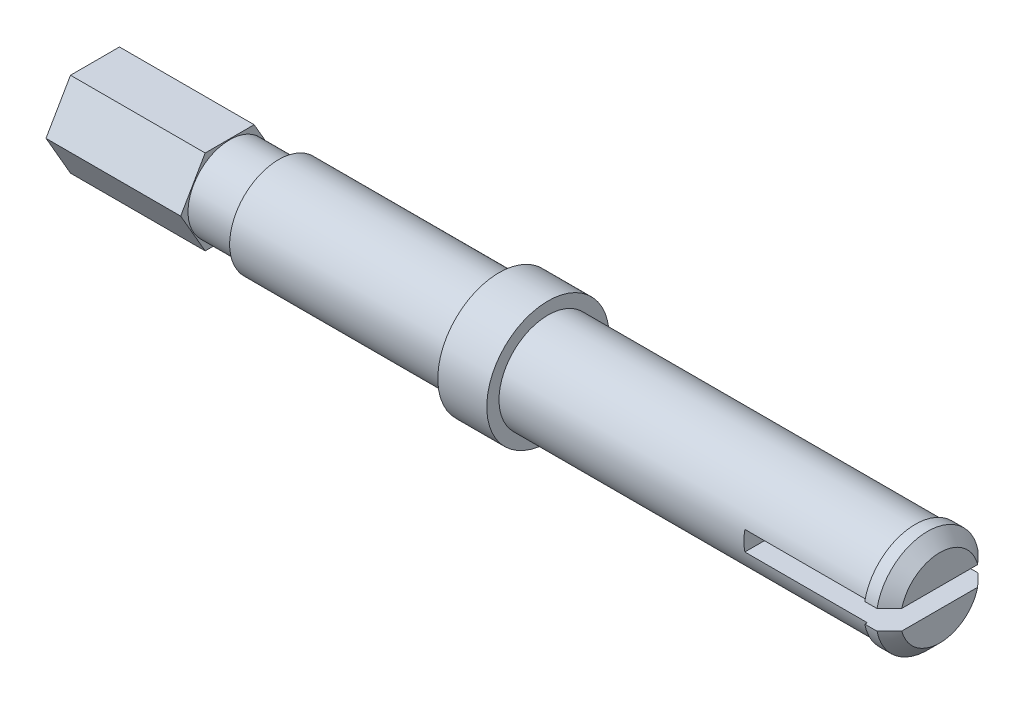
SolidWorks part; units mm, degrees
ref_plane "前视基准面" through (0, 0, 0) normal (0, 0, 1) x (1, 0, 0)
ref_plane "上视基准面" through (0, 0, 0) normal (0, 1, 0) x (1, 0, 0)
ref_plane "右视基准面" through (0, 0, 0) normal (1, 0, 0) x (0, 0, -1)
sketch "草图1" plane through (0, 0, 0) normal (1, 0, 0) x (0, 0, -1)
  line L1 (-2, 0) -> (-1, -1.7321)
  line L2 (-1, -1.7321) -> (1, -1.7321)
  line L3 (1, -1.7321) -> (2, 0)
  line L4 (2, 0) -> (1, 1.7321)
  line L5 (1, 1.7321) -> (-1, 1.7321)
  line L6 (-1, 1.7321) -> (-2, 0)
  circle A0 centre (0, 0) radius 1.7321 construction
  dimension "D1" = 4
extrude "凸台-拉伸1" add sketch "草图1" along normal blind 5.5
sketch "草图2" plane through (5.5, 0, 0) normal (1, 0, 0) x (0, 0, -1)
  circle A0 centre (0, 0) radius 1.7
  dimension "D1" = 3.4
extrude "凸台-拉伸2" add sketch "草图2" along normal blind 2
sketch "草图3" plane through (7.5, 0, 0) normal (1, 0, 0) x (0, 0, -1)
  circle A0 centre (0, 0) radius 2
  dimension "D1" = 4
extrude "凸台-拉伸3" add sketch "草图3" along normal blind 9
sketch "草图4" plane through (16.5, 0, 0) normal (1, 0, 0) x (0, 0, -1)
  circle A0 centre (0, 0) radius 2.5
  dimension "D1" = 5
extrude "凸台-拉伸4" add sketch "草图4" along normal blind 2
sketch "草图5" plane through (18.5, 0, 0) normal (1, 0, 0) x (0, 0, -1)
  circle A0 centre (0, 0) radius 2
  dimension "D1" = 4
extrude "凸台-拉伸5" add sketch "草图5" along normal blind 16
sketch "草图6" plane through (34.5, 0, 0) normal (1, 0, 0) x (0, 0, -1)
  circle A0 centre (0, 0) radius 2.1
  dimension "D1" = 4.2
extrude "凸台-拉伸6" add sketch "草图6" against normal blind 1
chamfer "倒角1" distance 0.5 angle 45 1 edges at (34.5, 0, -2.1)
sketch "草图7" plane through (34.5, 0, 0) normal (1, 0, 0) x (0, 0, -1)
  line L0 (2.5, 0.4) -> (2.5, -0.4)
  line L1 (2.5, 0.4) -> (-2.5, 0.4)
  line L2 (2.5, -0.4) -> (-2.5, -0.4)
  line L3 (-2.5, 0.4) -> (-2.5, -0.4)
  line L4 (2.5, 0.4) -> (-2.5, -0.4) construction
  line L5 (2.5, -0.4) -> (-2.5, 0.4) construction
  point P1 (0, 0)
  dimension "D1" = 0.8
  dimension "D2" = 5
extrude "切除-拉伸1" cut sketch "草图7" against normal blind 6
